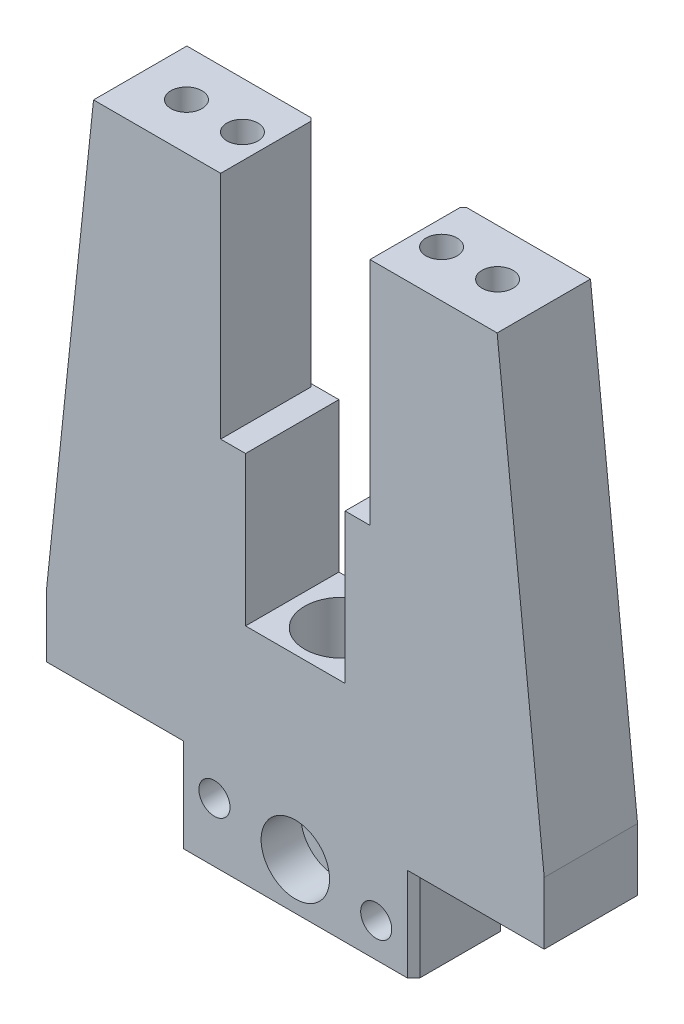
SolidWorks part; units mm, degrees
ref_plane "Piano frontale" through (0, 0, 0) normal (0, 0, 1) x (1, 0, 0)
ref_plane "Piano superiore" through (0, 0, 0) normal (0, 1, 0) x (1, 0, 0)
ref_plane "Piano destro" through (0, 0, 0) normal (1, 0, 0) x (0, 0, -1)
sketch "Schizzo1" plane through (0, 0, 0) normal (0, 0, 1) x (1, 0, 0)
  line L0 (0, 0) -> (0, 106.6303) construction
  line L1 (19, 0) -> (-19, 0)
  line L2 (-19, 0) -> (-19, 15)
  line L3 (-19, 15) -> (-40, 15)
  line L4 (-40, 15) -> (-40, 25)
  line L5 (-40, 25) -> (-32.4325, 97)
  line L6 (-32.4325, 97) -> (-12, 97)
  line L7 (-12, 97) -> (-12, 60)
  line L8 (-12, 60) -> (-8, 60)
  line L9 (-8, 60) -> (-8, 36)
  line L10 (-8, 36) -> (8, 36)
  line L11 (8, 60) -> (8, 36)
  line L12 (12, 60) -> (8, 60)
  line L13 (12, 97) -> (12, 60)
  line L14 (32.4325, 97) -> (12, 97)
  line L15 (40, 25) -> (32.4325, 97)
  line L16 (40, 15) -> (40, 25)
  line L17 (19, 15) -> (40, 15)
  line L18 (19, 0) -> (19, 15)
  point P14 (0, 36)
  dimension "D1" = 38
  dimension "D2" = 80
  dimension "D3" = 15
  dimension "D4" = 10
  dimension "D5" = 82
  dimension "D6" = 24
  dimension "D7" = 16
  dimension "D8" = 37
  dimension "D9" = 61
  dimension "D10" = 6
extrude "Estrusione-Estrusione1" add sketch "Schizzo1" along normal blind 15
hole_wizard "Foro Ø5.0 (5)-1" positions "Schizzo4" profile "Schizzo3" hole size "Ø5.0" standard "ISO"
sketch "Schizzo4" plane through (0, 97, 0) normal (0, 1, 0) x (1, 0, 0)
  line L0 (8, -15) -> (-8, -15) construction
  line L1 (-12, 0) -> (-32.4325, 0) construction
  point P0 (-16, -7.5)
  point P2 (16, -7.5)
  point P6 (0, -15)
  dimension "D1" = 16
  dimension "D2" = 16
  dimension "D3" = 7.5
sketch "Schizzo3" plane through (-16, 97, 7.5) normal (1, 0, 0) x (0, 0, 1)
  line L0 (0, 0) -> (0, 17.5022)
  line L1 (0, 17.5022) -> (2.5, 16)
  line L2 (2.5, 16) -> (2.5, 0)
  line L5 (2.5, 0) -> (0, 0)
  line L10 (0, 17.5022) -> (-2.5, 16) construction
  line L11 (0, -6.35) -> (0, 107.95) construction
  dimension "Hole Dia." = 5
  dimension "Hole Depth" = 16
  dimension "Drill Angle" = 118
hole_wizard "Foro filettato M6-1" positions "Schizzo6" profile "Schizzo5" tap size "M6" standard "ISO"
sketch "Schizzo6" plane through (0, 97, 0) normal (0, 1, 0) x (1, 0, 0)
  point P0 (-25, -7.5)
  point P2 (25, -7.5)
  dimension "D1" = 25
  dimension "D2" = 50
sketch "Schizzo5" plane through (-25, 97, 7.5) normal (1, 0, 0) x (0, 0, 1)
  line L0 (0, 0) -> (0, 21.5022)
  line L1 (0, 21.5022) -> (2.5, 20)
  line L2 (2.5, 20) -> (2.5, 0)
  line L5 (2.5, 0) -> (0, 0)
  line L10 (0, 21.5022) -> (-2.5, 20) construction
  line L11 (0, -6.35) -> (0, 107.95) construction
  dimension "Tap Drill Dia." = 5
  dimension "Tap Drill Depth" = 20
  dimension "Drill Angle" = 118
cosmetic thread "Filettatura del foro1" parameters "D1"=15, "D2"=6
cosmetic thread "Filettatura del foro2" parameters "D1"=15, "D2"=6
sketch "Schizzo7" plane through (0, 36, 0) normal (0, 1, 0) x (1, 0, 0)
  line L0 (8, -15) -> (-8, -15) construction
  line L1 (0, -15) -> (0, 0) construction
  circle A0 centre (0, -7.5) radius 6
  dimension "D1" = 12
extrude "Taglio-Estrusione1" cut sketch "Schizzo7" against normal blind 16.5
hole_wizard "Foro Ø5.0 (5)-2" positions "Schizzo9" profile "Schizzo8" hole size "Ø5.0" standard "ISO" end condition through all
sketch "Schizzo9" plane through (0, 0, 0) normal (0, 0, -1) x (-1, 0, 0)
  line L0 (0, 36) -> (0, -4.7495) construction
  line L1 (-8, 36) -> (8, 36) construction
  line L3 (-19, 7.5) -> (19, 7.5) construction
  line L4 (-19, 0) -> (-19, 15) construction
  line L5 (19, 15) -> (19, 0) construction
  point P0 (-13, 5.5)
  point P2 (13, 9.5)
  dimension "D1" = 13
  dimension "D2" = 26
  dimension "D3" = 2
  dimension "D4" = 4
sketch "Schizzo8" plane through (13, 5.5, 0) normal (1, 0, 0) x (0, 1, 0)
  line L0 (0, 0) -> (0, 15)
  line L1 (0, 15) -> (2.5, 15)
  line L2 (2.5, 15) -> (2.5, 0)
  line L5 (2.5, 0) -> (0, 0)
  line L11 (0, -6.35) -> (0, 107.95) construction
  dimension "Thru Hole Dia." = 5
  dimension "Thru Hole Depth" = 15
hole_wizard "Foro lamato per Vite M6 a testa cilindrica-1" positions "Schizzo11" profile "Schizzo10" counterbore size "M6" standard "ISO" end condition through all
sketch "Schizzo11" plane through (0, 0, 15) normal (0, 0, 1) x (1, 0, 0)
  line L0 (19, 7.5) -> (-19, 7.5) construction
  point P0 (0, 7.5)
sketch "Schizzo10" plane through (0, 7.5, 15) normal (1, 0, 0) x (0, -1, 0)
  line L0 (0, 0) -> (0, 15)
  line L1 (0, 15) -> (3.3, 15)
  line L3 (3.3, 15) -> (3.3, 6.4)
  line L4 (3.3, 6.4) -> (5.5, 6.4)
  line L5 (5.5, 6.4) -> (5.5, 0)
  line L7 (5.5, 0) -> (0, 0)
  line L11 (0, -6.35) -> (0, 107.95) construction
  dimension "Thru Hole Dia." = 6.6
  dimension "Thru Hole Depth" = 15
  dimension "C'Bore Dia." = 11
  dimension "C'Bore Depth" = 6.4
chamfer "Smusso1" distance 1 angle 45 4 edges at (19, 7.5, 0) (-19, 7.5, 0) (19, 7.5, 15) (-19, 7.5, 15)
chamfer "Smusso2" distance 0.5 angle 45 2 edges at (-12, 78.5, 0) (12, 78.5, 0)
